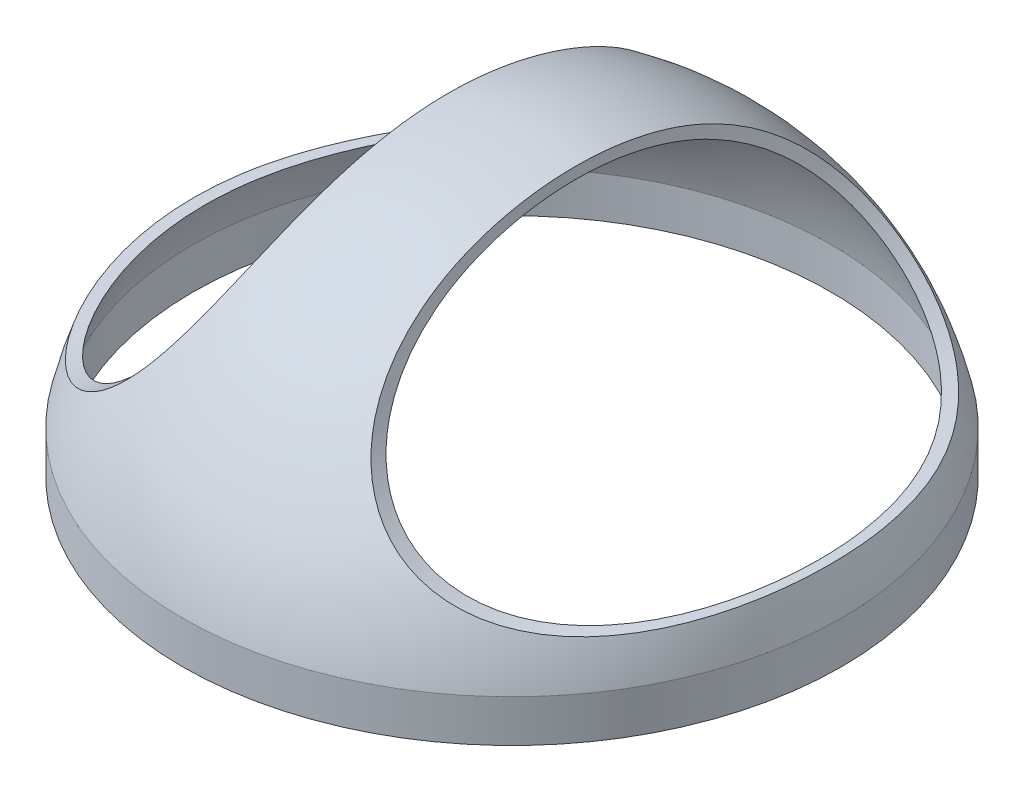
SolidWorks part; units mm, degrees
ref_plane "前视基准面" through (0, 0, 0) normal (0, 0, 1) x (1, 0, 0)
ref_plane "上视基准面" through (0, 0, 0) normal (0, 1, 0) x (1, 0, 0)
ref_plane "右视基准面" through (0, 0, 0) normal (1, 0, 0) x (0, 0, -1)
other "Configuration Table"
sketch "草图7" plane through (0, 0, 0) normal (0, 0, 1) x (1, 0, 0)
  line L0 (0, 32) -> (0, -1.5)
  line L1 (0, 7) -> (31.225, 7)
  line L2 (31.225, 7) -> (31.225, 3)
  line L3 (31.225, 3) -> (0, 3)
  arc A0 (31.225, 7) -> (0, 32) centre (0, 0) ccw
  dimension "D1" = 25
  dimension "D2" = 29
revolve "旋转12" add sketch "草图7" angle 360 about L0
shell "抽壳2" thickness 1
sketch "草图9" plane through (0, 0, 0) normal (0, 0, 1) x (1, 0, 0)
  line L0 (0, 0) -> (0, 32)
  arc A0 (30.1134, 10.8252) -> (6.0076, 31.431) centre (0, 0) ccw
  arc A1 (6.0076, 31.431) -> (30.1134, 10.8252) centre (27.3538, 32) ccw
  arc A2 (-30.1134, 10.8252) -> (-6.0076, 31.431) centre (0, 0) cw
  arc A3 (-6.0076, 31.431) -> (-30.1134, 10.8252) centre (-27.3538, 32) cw
  point P7 (0, 32)
extrude "切除-拉伸4" cut sketch "草图9" against normal through all both and the other way through all contours A3 A2 | A0 A1
